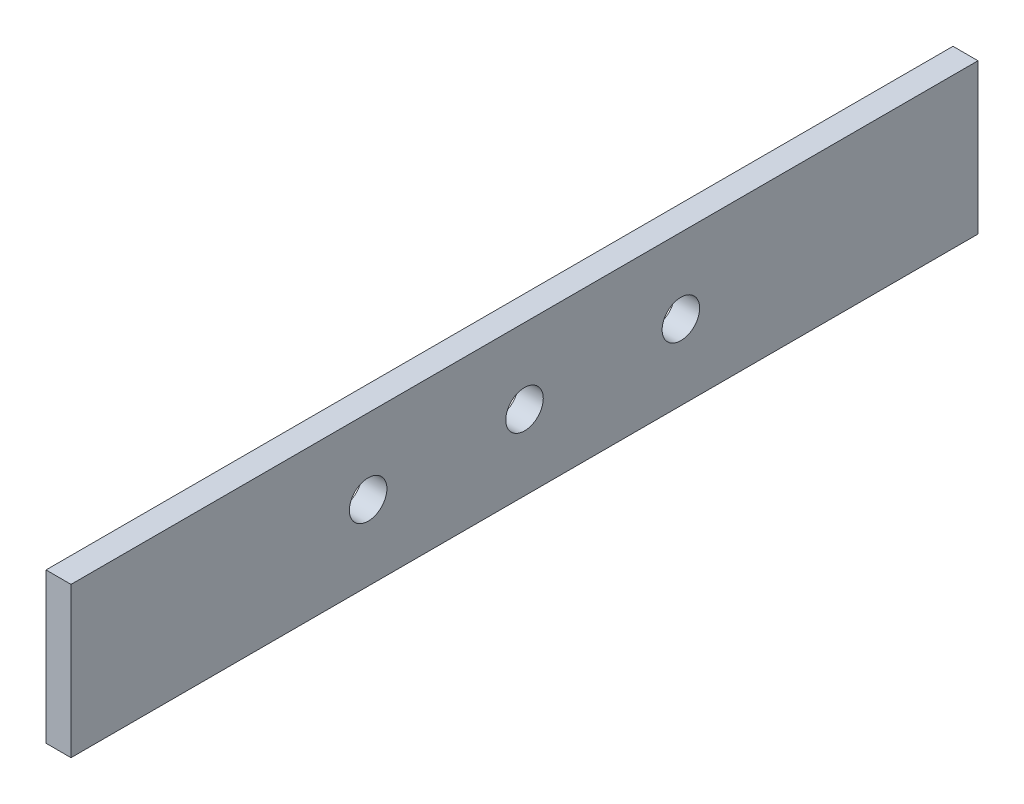
SolidWorks part; units mm, degrees
ref_plane "Front Plane" through (0, 0, 0) normal (0, 0, 1) x (1, 0, 0)
ref_plane "Top Plane" through (0, 0, 0) normal (0, 1, 0) x (1, 0, 0)
ref_plane "Right Plane" through (0, 0, 0) normal (1, 0, 0) x (0, 0, -1)
sketch "Sketch1" plane through (0, 0, 0) normal (1, 0, 0) x (0, 0, -1)
  line L0 (-23.7476, 0) -> (48.7524, 0)
  line L1 (55, 0) -> (-55, 0) construction
  line L2 (48.7524, 0) -> (48.7524, 12)
  line L3 (48.7524, 12) -> (-23.7476, 12)
  line L4 (-23.7476, 12) -> (-23.7476, 0)
extrude "Boss-Extrude1" add sketch "Sketch1" along normal blind 2
sketch "Sketch3" plane through (2, 0, 0) normal (1, 0, 0) x (0, 0, -1)
  line L0 (-23.7476, 6) -> (48.7524, 6) construction
  line L1 (-23.7476, 12) -> (-23.7476, 0) construction
  line L2 (48.7524, 0) -> (48.7524, 12) construction
  circle A0 centre (12.5024, 6) radius 1.5
  circle A1 centre (0.0024, 6) radius 1.5
  circle A2 centre (25.0024, 6) radius 1.5
  dimension "D1" = 12.5
  dimension "D2" = 12.5
extrude "Cut-Extrude1" cut sketch "Sketch3" along direction (1, 0, 0) on the side against the normal up to next (2 mm away)
